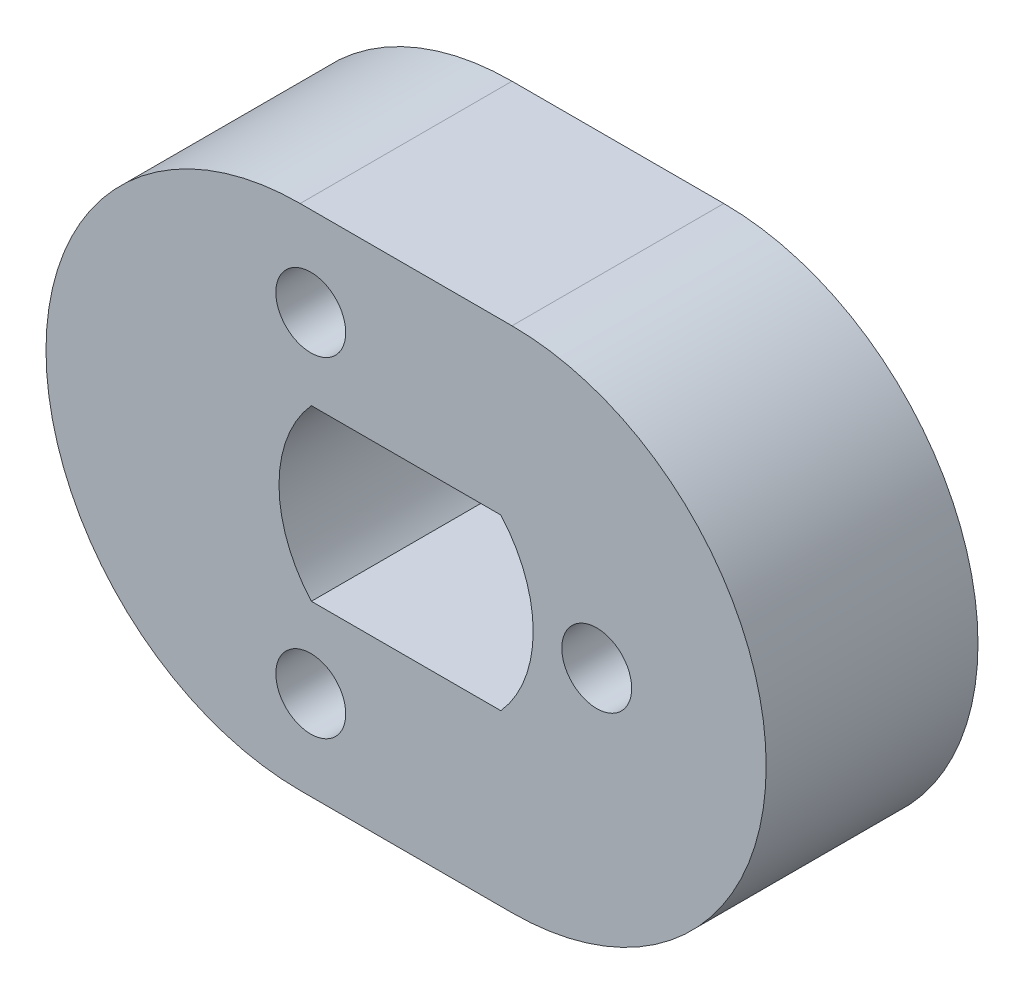
SolidWorks part; units mm, degrees
ref_plane "Front Plane" through (0, 0, 0) normal (0, 0, 1) x (1, 0, 0)
ref_plane "Top Plane" through (0, 0, 0) normal (0, 1, 0) x (1, 0, 0)
ref_plane "Right Plane" through (0, 0, 0) normal (1, 0, 0) x (0, 0, -1)
sketch "Sketch1" plane through (0, 0, 0) normal (0, 0, 1) x (1, 0, 0)
  line L0 (0, 0) -> (10, 0) construction
  line L1 (0, 12) -> (10, 12)
  line L2 (0, -12) -> (10, -12)
  arc A0 (0, 12) -> (0, -12) centre (0, 0) ccw
  arc A1 (10, -12) -> (10, 12) centre (10, 0) ccw
  circle A2 centre (5, 0) radius 6
  point P3 (5, 0)
  dimension "D1" = 12
  dimension "D2" = 10
  dimension "D3" = 12
extrude "Boss-Extrude1" add sketch "Sketch1" along normal blind 10
sketch "Sketch2" plane through (0, 0, 10) normal (0, 0, 1) x (1, 0, 0)
  circle A0 centre (5, 0) radius 9
  point P3 (14, 0)
  dimension "D1" = 18
hole_wizard "M4 Tapped Hole1" positions "3DSketch1" profile "Sketch3" tap size "M4" standard "ISO" end condition through all
sketch3d "3DSketch1"
  point P0 (14, 0, 10)
sketch "Sketch3" plane through (14, 0, 10) normal (1, 0, 0) x (0, -1, 0)
  line L0 (0, 0) -> (0, 10)
  line L1 (0, 10) -> (1.65, 10)
  line L2 (1.65, 10) -> (1.65, 0)
  line L5 (1.65, 0) -> (0, 0)
  line L11 (0, -6.35) -> (0, 107.95) construction
  dimension "Thru Tap Drill Dia." = 3.3
  dimension "Thru Tap Drill Depth" = 10
cosmetic thread "Hole Thread2" parameters "D2"=4
pattern_circular "CirPattern1" count 3 every 120 about axis through (5, 0, 0) along (0, 0, 1) of "M4 Tapped Hole1"
sketch "Sketch4" plane through (0, 0, 10) normal (0, 0, 1) x (1, 0, 0)
  line L0 (0.5279, 4) -> (9.4721, 4)
  line L1 (0.5279, -4) -> (9.4721, -4)
  circle A0 centre (5, 0) radius 6 construction
  arc A1 (9.4721, 4) -> (9.4721, -4) centre (5, 0) ccw
  circle M10 centre (5, 0) radius 6
  dimension "D1" = 8
  dimension "D2" = 4
extrude "Boss-Extrude2" add sketch "Sketch4" against normal blind 10 contours L0 M10 | L1 M10
